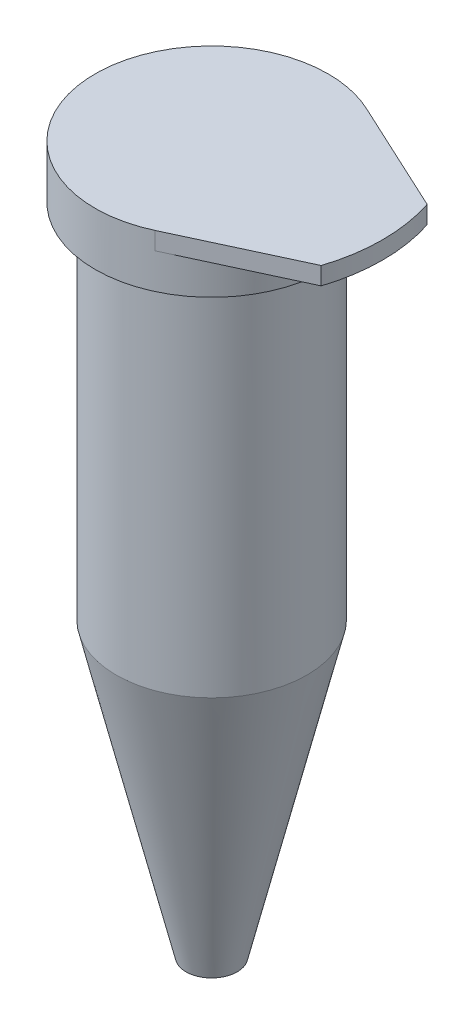
SolidWorks part; units mm, degrees
ref_plane "Alzado" through (0, 0, 0) normal (0, 0, 1) x (1, 0, 0)
ref_plane "Planta" through (0, 0, 0) normal (0, 1, 0) x (1, 0, 0)
ref_plane "Vista lateral" through (0, 0, 0) normal (1, 0, 0) x (0, 0, -1)
sketch "Croquis1" plane through (0, 0, 0) normal (0, 0, 1) x (1, 0, 0)
  line L0 (0, 0) -> (0, 40.1471) construction
  line L1 (0, 40.5) -> (0, 0)
  line L2 (0, 40.5) -> (6.6, 40.5)
  line L3 (6.6, 40.5) -> (6.6, 37.5)
  line L4 (6.6, 37.5) -> (5.4, 37.5)
  line L5 (5.4, 37.5) -> (5.4, 17)
  line L7 (5.4, 17) -> (1.4519, 0.4648)
  arc A1 (0, 0) -> (1.4519, 0.4648) centre (0, 2.5) ccw
  dimension "D6" = 2.5
  dimension "D1" = 3
  dimension "D2" = 1.2
  dimension "D3" = 6.6
  dimension "D4" = 20.5
  dimension "D5" = 40.5
  dimension "D7" = 17
revolve "Revolución1" add sketch "Croquis1" angle 360 about L0
sketch "Croquis2" plane through (0, 40.5, 0) normal (0, 1, 0) x (1, 0, 0)
  line L0 (9.209, 3) -> (2.7801, 5.9859)
  line L1 (9.209, -3) -> (2.7801, -5.9859)
  arc A0 (9.209, -3) -> (9.209, 3) centre (0, 0) ccw
  circle A1 centre (0, 0) radius 6.6 construction
  arc A2 (2.7801, -5.9859) -> (2.7801, 5.9859) centre (0, 0) ccw
  point P4 (9.6854, 0)
  dimension "D1" = 6
extrude "Saliente-Extruir1" add sketch "Croquis2" against normal blind 1
